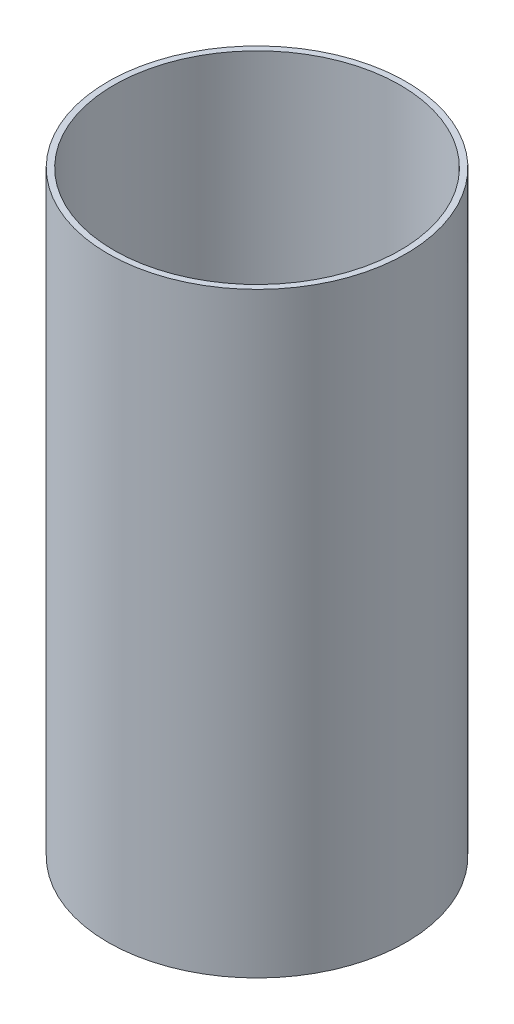
SolidWorks part; units mm, degrees
ref_plane "Plan de face" through (0, 0, 0) normal (0, 0, 1) x (1, 0, 0)
ref_plane "Plan de dessus" through (0, 0, 0) normal (0, 1, 0) x (1, 0, 0)
ref_plane "Plan de droite" through (0, 0, 0) normal (1, 0, 0) x (0, 0, -1)
sketch "Esquisse1" plane through (0, 0, 0) normal (0, 1, 0) x (1, 0, 0)
  circle A0 centre (0, 0) radius 75
  circle A1 centre (0, 0) radius 72
  dimension "D1" = 150
  dimension "D2" = 3
extrude "Boss.-Extru.1" add sketch "Esquisse1" along normal blind 300
ref_plane "Plan1" through (0, 150, 0) normal (0, -1, 0) x (-1, 0, 0)
